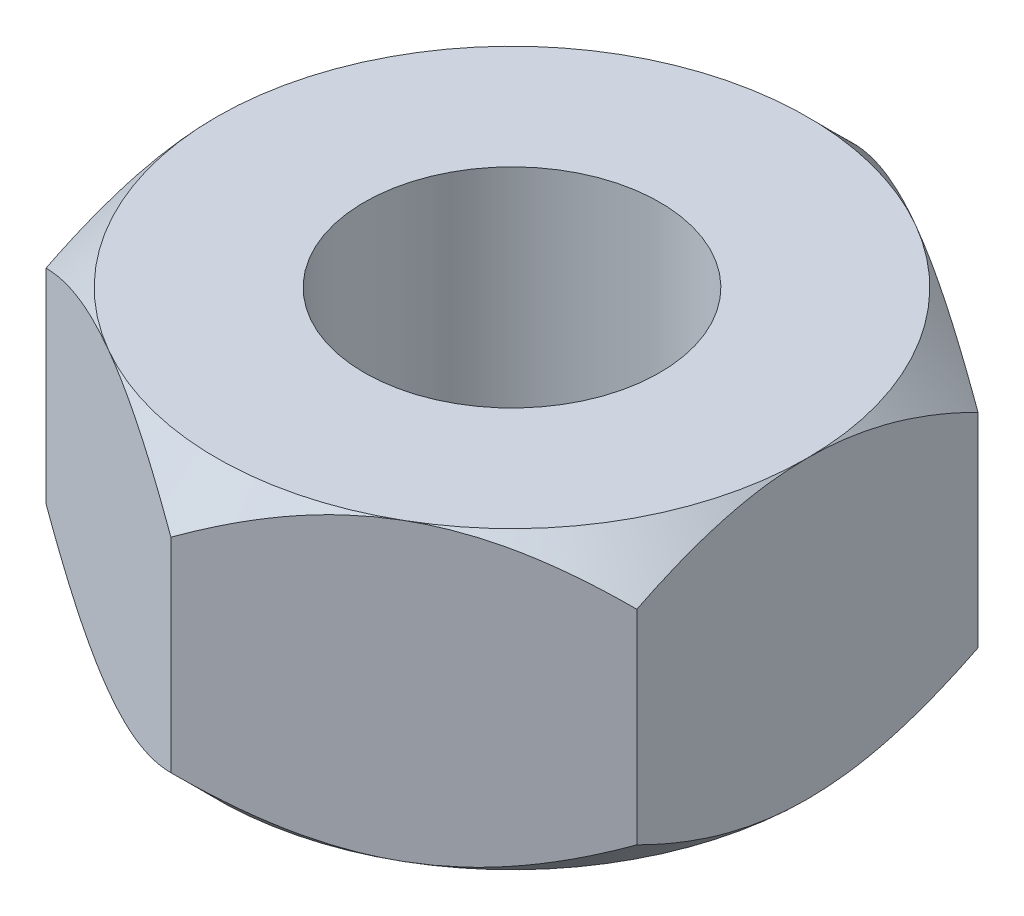
SolidWorks part; units mm, degrees
material "Plain Carbon Steel"
ref_plane "Front Plane" through (0, 0, 0) normal (0, 0, 1) x (1, 0, 0)
ref_plane "Top Plane" through (0, 0, 0) normal (0, 1, 0) x (1, 0, 0)
ref_plane "Right Plane" through (0, 0, 0) normal (1, 0, 0) x (0, 0, -1)
sketch "Sketch1" plane through (0, 0, 0) normal (0, 1, 0) x (1, 0, 0)
  line L1 (0, 3.4641) -> (-3, 1.7321)
  line L2 (-3, 1.7321) -> (-3, -1.7321)
  line L3 (-3, -1.7321) -> (0, -3.4641)
  line L4 (0, -3.4641) -> (3, -1.7321)
  line L5 (3, -1.7321) -> (3, 1.7321)
  line L6 (3, 1.7321) -> (0, 3.4641)
  circle A0 centre (0, 0) radius 1.5
  circle A1 centre (0, 0) radius 3 construction
  dimension "D1" = 3
  dimension "D2" = 6
extrude "Boss-Extrude1" add sketch "Sketch1" along normal mid plane 3
sketch "Sketch2" plane through (0, 1.5, 0) normal (0, 1, 0) x (1, 0, 0)
  line L0 (-3, 1.7321) -> (-3, -1.7321) construction
  circle A0 centre (0, 0) radius 3
sketch "Sketch3" plane through (0, 0, 0) normal (0, 0, 1) x (1, 0, 0)
  line L0 (-3.5, 1) -> (-3, 1.5)
  line L3 (-3, 1.5) -> (-3.5, 1.5)
  line L4 (-3.5, 1.5) -> (-3.5, 1)
  dimension "D1" = 0.5
  dimension "D2" = 0.5
sweep "Cut-Sweep1" cut profiles "Sketch3" path "Sketch2"
mirror "Mirror1" about plane through (0, 0, 0) normal (0, 1, 0) of "Cut-Sweep1"
